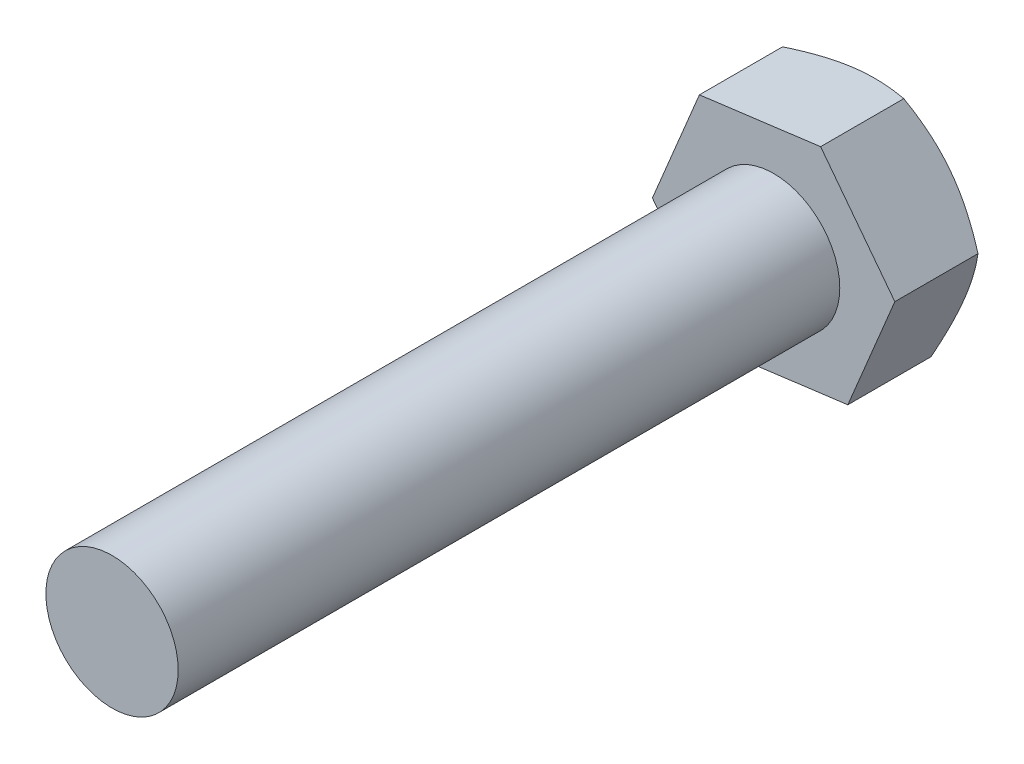
SolidWorks part; units mm, degrees
ref_plane "Front Plane" through (0, 0, 0) normal (0, 0, 1) x (1, 0, 0)
ref_plane "Top Plane" through (0, 0, 0) normal (0, 1, 0) x (1, 0, 0)
ref_plane "Right Plane" through (0, 0, 0) normal (1, 0, 0) x (0, 0, -1)
sketch "Sketch1" plane through (0, 0, 0) normal (0, 0, 1) x (1, 0, 0)
  line L1 (1.7761, 4.2637) -> (-2.8044, 3.67)
  line L2 (-2.8044, 3.67) -> (-4.5805, -0.5937)
  line L3 (-4.5805, -0.5937) -> (-1.7761, -4.2637)
  line L4 (-1.7761, -4.2637) -> (2.8044, -3.67)
  line L5 (2.8044, -3.67) -> (4.5805, 0.5937)
  line L6 (4.5805, 0.5937) -> (1.7761, 4.2637)
  circle A0 centre (0, 0) radius 4 construction
  dimension "D1" = 8
extrude "Boss-Extrude1" add sketch "Sketch1" along normal blind 3.5
sketch "Sketch2" plane through (0, 0, 0) normal (0, 0, -1) x (-1, 0, 0)
  circle A0 centre (0, 0) radius 4
  dimension "D1" = 8
extrude "Cut-Extrude1" cut sketch "Sketch2" against normal blind 5 draft 60 flip side to cut
sketch "Sketch3" plane through (0, 0, 3.5) normal (0, 0, 1) x (1, 0, 0)
  circle A0 centre (0, 0) radius 2.5
  dimension "D1" = 5
extrude "Boss-Extrude2" add sketch "Sketch3" along normal blind 25
sketch "Sketch6" plane through (0, 0, 28.5) normal (0, 0, 1) x (1, 0, 0)
  circle A0 centre (0, 0) radius 2.5
  dimension "D1" = 5
